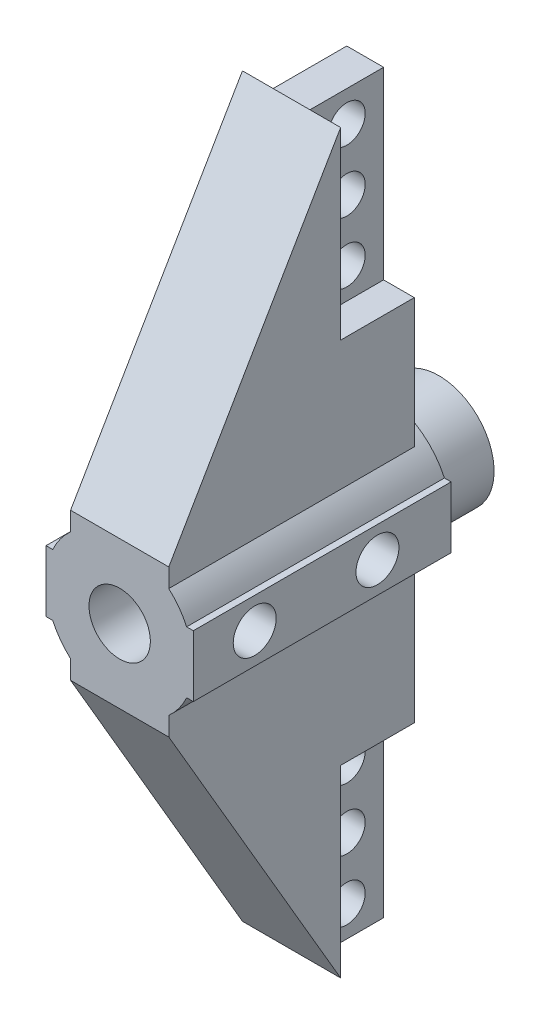
SolidWorks part; units mm, degrees
ref_plane "Front Plane" through (0, 0, 0) normal (0, 0, 1) x (1, 0, 0)
ref_plane "Top Plane" through (0, 0, 0) normal (0, 1, 0) x (1, 0, 0)
ref_plane "Right Plane" through (0, 0, 0) normal (1, 0, 0) x (0, 0, -1)
other "Configuration Table"
sketch "Sketch1" plane through (0, 0, 0) normal (0, 0, 1) x (1, 0, 0)
  circle A0 centre (0, 0) radius 2.5
  circle A1 centre (0, 0) radius 6
  dimension "D1" = 5
  dimension "D2" = 12
extrude "Boss-Extrude1" add sketch "Sketch1" along normal blind 20
sketch "Sketch2" plane through (0, 0, 0) normal (1, 0, 0) x (0, 0, -1)
  line L0 (-20, 6) -> (-20, 3)
  line L2 (-20, 3) -> (0, 3)
  line L3 (-20, 6) -> (-20, -6) construction
  line L5 (0, 3) -> (0, 30)
  line L6 (-20, 6) -> (-6, 30)
  line L7 (-6, 30) -> (0, 30)
  line L8 (0, 6) -> (-20, 6) construction
  dimension "D1" = 30
  dimension "D2" = 6
  dimension "D3" = 3
extrude "Boss-Extrude2" add sketch "Sketch2" along normal mid plane 8
sketch "Sketch3" plane through (0, 30, 0) normal (0, 1, 0) x (1, 0, 0)
  line L0 (-4, 0) -> (-1.5, 0)
  line L1 (4, 0) -> (-4, 0) construction
  line L2 (-1.5, 0) -> (-1.5, -6)
  line L3 (4, -6) -> (-4, -6) construction
  line L4 (-1.5, -6) -> (-4, -6)
  line L5 (-4, -6) -> (-4, 0)
  line L6 (4, 0) -> (1.5, 0)
  line L7 (1.5, 0) -> (1.5, -6)
  line L8 (1.5, -6) -> (4, -6)
  line L9 (4, -6) -> (4, 0)
  dimension "D1" = 2.5
extrude "Cut-Extrude1" cut sketch "Sketch3" against normal blind 15
sketch "Sketch9" plane through (-1.5, 0, 0) normal (-1, 0, 0) x (0, 0, 1)
  circle A1 centre (3, 17.5) radius 1.5
  circle A2 centre (3, 22.5) radius 1.5
  circle A3 centre (3, 27.5) radius 1.5
  dimension "D5" = 5
  dimension "D4" = 5
move or copy body "Body-Move/Copy1" bodies to move or copy 104 copy yes number of copies 1 rotation origin (0, 0, 0) rotation axis (0, 0, 1) rotation angle 180
sketch "Sketch4" plane through (0, 0, 0) normal (0, 0, -1) x (-1, 0, 0)
  circle A0 centre (0, 0) radius 6
extrude "Boss-Extrude3" add sketch "Sketch4" along normal blind 1
sketch "Sketch5" plane through (0, 0, -1) normal (0, 0, -1) x (-1, 0, 0)
  circle A0 centre (0, 0) radius 4.5
extrude "Boss-Extrude4" add sketch "Sketch5" along normal blind 5
sketch "Sketch6" plane through (0, 0, -6) normal (0, 0, -1) x (-1, 0, 0)
  circle A0 centre (0, 0) radius 3.5
extrude "Cut-Extrude2" cut sketch "Sketch6" against normal blind 5
sketch "Sketch7" plane through (0, 0, 20) normal (0, 0, 1) x (1, 0, 0)
  line L0 (-6, 2.5) -> (-6, -2.5)
  line L1 (-6, -2.5) -> (-4.9407, -2.5)
  line L2 (-4.9407, -2.5) -> (-4.9407, 2.5)
  line L3 (-4.9407, 2.5) -> (-6, 2.5)
  line L4 (6, -2.5) -> (6, 2.5)
  line L5 (6, 2.5) -> (4.6954, 2.5)
  line L6 (4.6954, 2.5) -> (4.6954, -2.5)
  line L7 (4.6954, -2.5) -> (6, -2.5)
  arc A0 (-4, 4.4721) -> (-4, -4.4721) centre (0, 0) ccw construction
  dimension "D1" = 2.5
extrude "Boss-Extrude5" add sketch "Sketch7" against normal blind 21
sketch "Sketch8" plane through (-6, 0, 0) normal (-1, 0, 0) x (0, 0, 1)
  line L0 (20, 2.5) -> (20, -2.5) construction
  circle A0 centre (5, 0) radius 1.75
  circle A1 centre (15, 0) radius 1.75
  dimension "D1" = 5
  dimension "D2" = 10
extrude "Cut-Extrude3" cut sketch "Sketch8" against normal through all
extrude "Cut-Extrude4" cut sketch "Sketch9" against normal through all
sketch "Sketch11" plane through (-1.5, 0, 0) normal (-1, 0, 0) x (0, 0, 1)
  circle A4 centre (3, -17.5) radius 1.5
  circle A5 centre (3, -22.5) radius 1.5
  circle A6 centre (3, -27.5) radius 1.5
  dimension "D4" = 5
  dimension "D5" = 5
extrude "Cut-Extrude5" cut sketch "Sketch11" against normal through all
